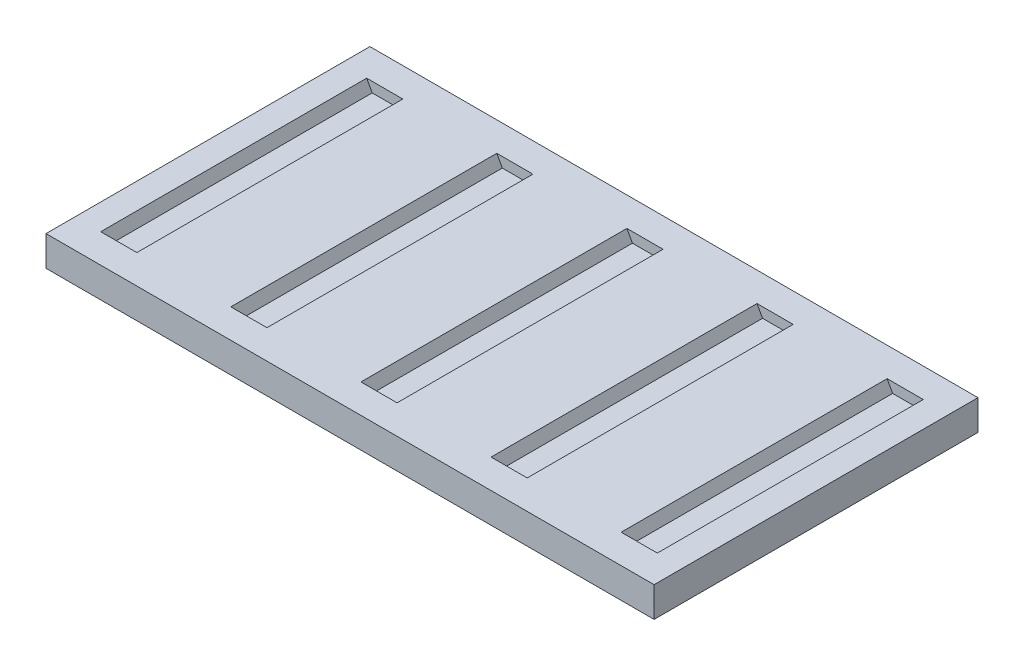
SolidWorks part; units mm, degrees
material "ABS"
ref_plane "Front Plane" through (0, 0, 0) normal (0, 0, 1) x (1, 0, 0)
ref_plane "Top Plane" through (0, 0, 0) normal (0, 1, 0) x (1, 0, 0)
ref_plane "Right Plane" through (0, 0, 0) normal (1, 0, 0) x (0, 0, -1)
sketch "ｽｹｯﾁ1" plane through (0, 0, 0) normal (0, 0, 1) x (1, 0, 0)
  line L0 (0, 0) -> (167.7493, 0) construction
  line B0 (0, 6.1517) -> (0, -7.9464) construction
  line B1 (-3.1032, 0) -> (3.1032, 0)
  line B2 (3.1032, 0) -> (2.3481, -2.0746)
  line B3 (1.0607, -2.976) -> (-1.0607, -2.976)
  line B4 (-2.3481, -2.0746) -> (-3.1032, 0)
  arc B5 (2.3481, -2.0746) -> (1.0607, -2.976) centre (1.0607, -1.606) cw
  arc B6 (-1.0607, -2.976) -> (-2.3481, -2.0746) centre (-1.0607, -1.606) cw
sketch_block_instance "ﾌﾞﾛｯｸ1-1"
sketch_block "ﾌﾞﾛｯｸ1" parameters "D2"=1.37, "D1"=40
sketch "ｽｹｯﾁ3" plane through (0, 0, 0) normal (0, 0, 1) x (1, 0, 0)
  line L0 (0, 6.1517) -> (0, -7.9464) construction
  line L1 (-2.3481, -2.0746) -> (-3.1032, 0) construction
  line L2 (1.0607, -2.976) -> (-1.0607, -2.976) construction
  line L3 (3.1032, 0) -> (2.3481, -2.0746) construction
  line L4 (3.1032, 0) -> (9.5968, 0)
  line L5 (0, 0) -> (167.7493, 0) construction
  line L6 (10.3519, -2.0746) -> (9.5968, 0)
  line L7 (13.7607, -2.976) -> (11.6393, -2.976)
  line L8 (0, 6.1517) -> (0, -7.9464) construction
  line L9 (-2.3481, -2.0746) -> (-3.1032, 0)
  line L10 (1.0607, -2.976) -> (-1.0607, -2.976)
  line L11 (3.1032, 0) -> (2.3481, -2.0746)
  line L12 (15.8032, 0) -> (15.0481, -2.0746)
  line L13 (12.7, 6.1517) -> (12.7, -7.9464) construction
  line L14 (15.8032, 0) -> (22.2968, 0)
  line L15 (23.0519, -2.0746) -> (22.2968, 0)
  line L16 (26.4607, -2.976) -> (24.3393, -2.976)
  line L17 (28.5032, 0) -> (27.7481, -2.0746)
  line L18 (25.4, 6.1517) -> (25.4, -7.9464) construction
  line L19 (28.5032, 0) -> (34.9968, 0)
  line L20 (35.7519, -2.0746) -> (34.9968, 0)
  line L21 (39.1607, -2.976) -> (37.0393, -2.976)
  line L22 (41.2032, 0) -> (40.4481, -2.0746)
  line L23 (38.1, 6.1517) -> (38.1, -7.9464) construction
  line L24 (41.2032, 0) -> (47.6968, 0)
  line L25 (48.4519, -2.0746) -> (47.6968, 0)
  line L26 (51.8607, -2.976) -> (49.7393, -2.976)
  line L27 (53.9032, 0) -> (53.1481, -2.0746)
  line L28 (50.8, 6.1517) -> (50.8, -7.9464) construction
  line L29 (53.9032, 0) -> (60.3968, 0)
  line L30 (61.1519, -2.0746) -> (60.3968, 0)
  line L31 (64.5607, -2.976) -> (62.4393, -2.976)
  line L32 (66.6032, 0) -> (65.8481, -2.0746)
  line L33 (63.5, 6.1517) -> (63.5, -7.9464) construction
  line L34 (66.6032, 0) -> (73.0968, 0)
  line L35 (73.8519, -2.0746) -> (73.0968, 0)
  line L36 (77.2607, -2.976) -> (75.1393, -2.976)
  line L37 (79.3032, 0) -> (78.5481, -2.0746)
  line L38 (76.2, 6.1517) -> (76.2, -7.9464) construction
  line L39 (79.3032, 0) -> (85.7968, 0)
  line L40 (86.5519, -2.0746) -> (85.7968, 0)
  line L41 (89.9607, -2.976) -> (87.8393, -2.976)
  line L42 (92.0032, 0) -> (91.2481, -2.0746)
  line L43 (88.9, 6.1517) -> (88.9, -7.9464) construction
  line L44 (92.0032, 0) -> (98.4968, 0)
  line L45 (99.2519, -2.0746) -> (98.4968, 0)
  line L46 (102.6607, -2.976) -> (100.5393, -2.976)
  line L47 (104.7032, 0) -> (103.9481, -2.0746)
  line L48 (101.6, 6.1517) -> (101.6, -7.9464) construction
  line L49 (104.7032, 0) -> (111.1968, 0)
  line L50 (111.9519, -2.0746) -> (111.1968, 0)
  line L51 (115.3607, -2.976) -> (113.2393, -2.976)
  line L52 (117.4032, 0) -> (116.6481, -2.0746)
  line L53 (114.3, 6.1517) -> (114.3, -7.9464) construction
  line L54 (117.4032, 0) -> (123.8968, 0)
  line L55 (124.6519, -2.0746) -> (123.8968, 0)
  line L56 (128.0607, -2.976) -> (125.9393, -2.976)
  line L57 (130.1032, 0) -> (129.3481, -2.0746)
  line L58 (127, 6.1517) -> (127, -7.9464) construction
  line L59 (130.1032, 0) -> (136.5968, 0)
  line L60 (137.3519, -2.0746) -> (136.5968, 0)
  line L61 (140.7607, -2.976) -> (138.6393, -2.976)
  line L62 (142.8032, 0) -> (142.0481, -2.0746)
  line L63 (139.7, 6.1517) -> (139.7, -7.9464) construction
  line L64 (142.8032, 0) -> (149.2968, 0)
  line L65 (150.0519, -2.0746) -> (149.2968, 0)
  line L66 (153.4607, -2.976) -> (151.3393, -2.976)
  line L67 (155.5032, 0) -> (154.7481, -2.0746)
  line L68 (152.4, 6.1517) -> (152.4, -7.9464) construction
  line L69 (155.5032, 0) -> (161.9968, 0)
  line L70 (162.7519, -2.0746) -> (161.9968, 0)
  line L71 (166.1607, -2.976) -> (164.0393, -2.976)
  line L72 (168.2032, 0) -> (167.4481, -2.0746)
  line L73 (165.1, 6.1517) -> (165.1, -7.9464) construction
  line L74 (168.2032, 0) -> (174.6968, 0)
  line L75 (175.4519, -2.0746) -> (174.6968, 0)
  line L76 (178.8607, -2.976) -> (176.7393, -2.976)
  line L77 (180.9032, 0) -> (180.1481, -2.0746)
  line L78 (177.8, 6.1517) -> (177.8, -7.9464) construction
  line L79 (180.9032, 0) -> (187.3968, 0)
  line L80 (188.1519, -2.0746) -> (187.3968, 0)
  line L81 (191.5607, -2.976) -> (189.4393, -2.976)
  line L82 (193.6032, 0) -> (192.8481, -2.0746)
  line L83 (190.5, 6.1517) -> (190.5, -7.9464) construction
  line L84 (193.6032, 0) -> (200.0968, 0)
  line L85 (200.8519, -2.0746) -> (200.0968, 0)
  line L86 (204.2607, -2.976) -> (202.1393, -2.976)
  line L87 (206.3032, 0) -> (205.5481, -2.0746)
  line L88 (203.2, 6.1517) -> (203.2, -7.9464) construction
  line L89 (206.3032, 0) -> (212.7968, 0)
  line L90 (213.5519, -2.0746) -> (212.7968, 0)
  line L91 (216.9607, -2.976) -> (214.8393, -2.976)
  line L92 (219.0032, 0) -> (218.2481, -2.0746)
  line L93 (215.9, 6.1517) -> (215.9, -7.9464) construction
  line L94 (219.0032, 0) -> (225.4968, 0)
  line L95 (226.2519, -2.0746) -> (225.4968, 0)
  line L96 (229.6607, -2.976) -> (227.5393, -2.976)
  line L97 (231.7032, 0) -> (230.9481, -2.0746)
  line L98 (228.6, 6.1517) -> (228.6, -7.9464) construction
  line L99 (231.7032, 0) -> (238.1968, 0)
  line L100 (238.9519, -2.0746) -> (238.1968, 0)
  line L101 (242.3607, -2.976) -> (240.2393, -2.976)
  line L102 (244.4032, 0) -> (243.6481, -2.0746)
  line L103 (241.3, 6.1517) -> (241.3, -7.9464) construction
  line L104 (244.4032, 0) -> (250.8968, 0)
  arc A0 (-2.3481, -2.0746) -> (-1.0607, -2.976) centre (-1.0607, -1.606) ccw construction
  arc A1 (1.0607, -2.976) -> (2.3481, -2.0746) centre (1.0607, -1.606) ccw construction
  arc A2 (10.3519, -2.0746) -> (11.6393, -2.976) centre (11.6393, -1.606) ccw
  arc A3 (13.7607, -2.976) -> (15.0481, -2.0746) centre (13.7607, -1.606) ccw
  arc A4 (-2.3481, -2.0746) -> (-1.0607, -2.976) centre (-1.0607, -1.606) ccw
  arc A5 (1.0607, -2.976) -> (2.3481, -2.0746) centre (1.0607, -1.606) ccw
  arc A6 (23.0519, -2.0746) -> (24.3393, -2.976) centre (24.3393, -1.606) ccw
  arc A7 (26.4607, -2.976) -> (27.7481, -2.0746) centre (26.4607, -1.606) ccw
  arc A8 (35.7519, -2.0746) -> (37.0393, -2.976) centre (37.0393, -1.606) ccw
  arc A9 (39.1607, -2.976) -> (40.4481, -2.0746) centre (39.1607, -1.606) ccw
  arc A10 (48.4519, -2.0746) -> (49.7393, -2.976) centre (49.7393, -1.606) ccw
  arc A11 (51.8607, -2.976) -> (53.1481, -2.0746) centre (51.8607, -1.606) ccw
  arc A12 (61.1519, -2.0746) -> (62.4393, -2.976) centre (62.4393, -1.606) ccw
  arc A13 (64.5607, -2.976) -> (65.8481, -2.0746) centre (64.5607, -1.606) ccw
  arc A14 (73.8519, -2.0746) -> (75.1393, -2.976) centre (75.1393, -1.606) ccw
  arc A15 (77.2607, -2.976) -> (78.5481, -2.0746) centre (77.2607, -1.606) ccw
  arc A16 (86.5519, -2.0746) -> (87.8393, -2.976) centre (87.8393, -1.606) ccw
  arc A17 (89.9607, -2.976) -> (91.2481, -2.0746) centre (89.9607, -1.606) ccw
  arc A18 (99.2519, -2.0746) -> (100.5393, -2.976) centre (100.5393, -1.606) ccw
  arc A19 (102.6607, -2.976) -> (103.9481, -2.0746) centre (102.6607, -1.606) ccw
  arc A20 (111.9519, -2.0746) -> (113.2393, -2.976) centre (113.2393, -1.606) ccw
  arc A21 (115.3607, -2.976) -> (116.6481, -2.0746) centre (115.3607, -1.606) ccw
  arc A22 (124.6519, -2.0746) -> (125.9393, -2.976) centre (125.9393, -1.606) ccw
  arc A23 (128.0607, -2.976) -> (129.3481, -2.0746) centre (128.0607, -1.606) ccw
  arc A24 (137.3519, -2.0746) -> (138.6393, -2.976) centre (138.6393, -1.606) ccw
  arc A25 (140.7607, -2.976) -> (142.0481, -2.0746) centre (140.7607, -1.606) ccw
  arc A26 (150.0519, -2.0746) -> (151.3393, -2.976) centre (151.3393, -1.606) ccw
  arc A27 (153.4607, -2.976) -> (154.7481, -2.0746) centre (153.4607, -1.606) ccw
  arc A28 (162.7519, -2.0746) -> (164.0393, -2.976) centre (164.0393, -1.606) ccw
  arc A29 (166.1607, -2.976) -> (167.4481, -2.0746) centre (166.1607, -1.606) ccw
  arc A30 (175.4519, -2.0746) -> (176.7393, -2.976) centre (176.7393, -1.606) ccw
  arc A31 (178.8607, -2.976) -> (180.1481, -2.0746) centre (178.8607, -1.606) ccw
  arc A32 (188.1519, -2.0746) -> (189.4393, -2.976) centre (189.4393, -1.606) ccw
  arc A33 (191.5607, -2.976) -> (192.8481, -2.0746) centre (191.5607, -1.606) ccw
  arc A34 (200.8519, -2.0746) -> (202.1393, -2.976) centre (202.1393, -1.606) ccw
  arc A35 (204.2607, -2.976) -> (205.5481, -2.0746) centre (204.2607, -1.606) ccw
  arc A36 (213.5519, -2.0746) -> (214.8393, -2.976) centre (214.8393, -1.606) ccw
  arc A37 (216.9607, -2.976) -> (218.2481, -2.0746) centre (216.9607, -1.606) ccw
  arc A38 (226.2519, -2.0746) -> (227.5393, -2.976) centre (227.5393, -1.606) ccw
  arc A39 (229.6607, -2.976) -> (230.9481, -2.0746) centre (229.6607, -1.606) ccw
  arc A40 (238.9519, -2.0746) -> (240.2393, -2.976) centre (240.2393, -1.606) ccw
  arc A41 (242.3607, -2.976) -> (243.6481, -2.0746) centre (242.3607, -1.606) ccw
  dimension "D1" = 20
  dimension "D2" = 12.7
sketch "ｽｹｯﾁ4" plane through (0, 0, 0) normal (0, 0, 1) x (1, 0, 0)
  line L0 (0, 6.1517) -> (0, -7.9464) construction
  line L1 (1.0607, -2.976) -> (-1.0607, -2.976) construction
  line L2 (3.1032, 0) -> (2.3481, -2.0746) construction
  line L3 (3.1032, 0) -> (9.5968, 0) construction
  line L4 (10.3519, -2.0746) -> (9.5968, 0) construction
  line L5 (13.7607, -2.976) -> (11.6393, -2.976) construction
  line L6 (15.8032, 0) -> (15.0481, -2.0746) construction
  line L7 (15.8032, 0) -> (22.2968, 0) construction
  line L8 (23.0519, -2.0746) -> (22.2968, 0) construction
  line L9 (26.4607, -2.976) -> (24.3393, -2.976) construction
  line L10 (28.5032, 0) -> (27.7481, -2.0746) construction
  line L11 (28.5032, 0) -> (34.9968, 0) construction
  line L12 (35.7519, -2.0746) -> (34.9968, 0) construction
  line L13 (39.1607, -2.976) -> (37.0393, -2.976) construction
  line L14 (41.2032, 0) -> (40.4481, -2.0746) construction
  line L15 (41.2032, 0) -> (47.6968, 0) construction
  line L16 (48.4519, -2.0746) -> (47.6968, 0) construction
  line L17 (51.8607, -2.976) -> (49.7393, -2.976) construction
  line L18 (53.9032, 0) -> (53.1481, -2.0746) construction
  line L19 (53.9032, 0) -> (60.3968, 0) construction
  line L20 (61.1519, -2.0746) -> (60.3968, 0) construction
  line L21 (64.5607, -2.976) -> (62.4393, -2.976) construction
  line L22 (66.6032, 0) -> (65.8481, -2.0746) construction
  line L23 (66.6032, 0) -> (73.0968, 0) construction
  line L24 (73.8519, -2.0746) -> (73.0968, 0) construction
  line L25 (77.2607, -2.976) -> (75.1393, -2.976) construction
  line L26 (79.3032, 0) -> (78.5481, -2.0746) construction
  line L27 (79.3032, 0) -> (85.7968, 0) construction
  line L28 (86.5519, -2.0746) -> (85.7968, 0) construction
  line L29 (89.9607, -2.976) -> (87.8393, -2.976) construction
  line L30 (92.0032, 0) -> (91.2481, -2.0746) construction
  line L31 (92.0032, 0) -> (98.4968, 0) construction
  line L32 (99.2519, -2.0746) -> (98.4968, 0) construction
  line L33 (102.6607, -2.976) -> (100.5393, -2.976) construction
  line L34 (104.7032, 0) -> (103.9481, -2.0746) construction
  line L35 (104.7032, 0) -> (111.1968, 0) construction
  line L36 (111.9519, -2.0746) -> (111.1968, 0) construction
  line L37 (115.3607, -2.976) -> (113.2393, -2.976) construction
  line L38 (117.4032, 0) -> (116.6481, -2.0746) construction
  line L39 (117.4032, 0) -> (123.8968, 0) construction
  line L40 (124.6519, -2.0746) -> (123.8968, 0) construction
  line L41 (128.0607, -2.976) -> (125.9393, -2.976) construction
  line L42 (130.1032, 0) -> (129.3481, -2.0746) construction
  line L43 (130.1032, 0) -> (136.5968, 0) construction
  line L44 (137.3519, -2.0746) -> (136.5968, 0) construction
  line L45 (140.7607, -2.976) -> (138.6393, -2.976) construction
  line L46 (142.8032, 0) -> (142.0481, -2.0746) construction
  line L47 (142.8032, 0) -> (149.2968, 0) construction
  line L48 (150.0519, -2.0746) -> (149.2968, 0) construction
  line L49 (153.4607, -2.976) -> (151.3393, -2.976) construction
  line L50 (155.5032, 0) -> (154.7481, -2.0746) construction
  line L51 (155.5032, 0) -> (161.9968, 0) construction
  line L52 (162.7519, -2.0746) -> (161.9968, 0) construction
  line L53 (166.1607, -2.976) -> (164.0393, -2.976) construction
  line L54 (168.2032, 0) -> (167.4481, -2.0746) construction
  line L55 (168.2032, 0) -> (174.6968, 0) construction
  line L56 (175.4519, -2.0746) -> (174.6968, 0) construction
  line L57 (178.8607, -2.976) -> (176.7393, -2.976) construction
  line L58 (180.9032, 0) -> (180.1481, -2.0746) construction
  line L59 (180.9032, 0) -> (187.3968, 0) construction
  line L60 (188.1519, -2.0746) -> (187.3968, 0) construction
  line L61 (191.5607, -2.976) -> (189.4393, -2.976) construction
  line L62 (193.6032, 0) -> (192.8481, -2.0746) construction
  line L63 (193.6032, 0) -> (200.0968, 0) construction
  line L64 (200.8519, -2.0746) -> (200.0968, 0) construction
  line L65 (204.2607, -2.976) -> (202.1393, -2.976) construction
  line L66 (206.3032, 0) -> (205.5481, -2.0746) construction
  line L67 (206.3032, 0) -> (212.7968, 0) construction
  line L68 (213.5519, -2.0746) -> (212.7968, 0) construction
  line L69 (216.9607, -2.976) -> (214.8393, -2.976) construction
  line L70 (219.0032, 0) -> (218.2481, -2.0746) construction
  line L71 (219.0032, 0) -> (225.4968, 0) construction
  line L72 (226.2519, -2.0746) -> (225.4968, 0) construction
  line L74 (121.1804, 61.4098) -> (121.1804, -57.3786) construction
  line L75 (229.6607, -2.976) -> (227.5393, -2.976) construction
  line L76 (231.7032, 0) -> (230.9481, -2.0746) construction
  line L77 (1.0607, -2.976) -> (0, -2.976)
  line L78 (3.1032, 0) -> (2.3481, -2.0746)
  line L79 (3.1032, 0) -> (9.5968, 0)
  line L80 (10.3519, -2.0746) -> (9.5968, 0)
  line L81 (13.7607, -2.976) -> (11.6393, -2.976)
  line L82 (15.8032, 0) -> (15.0481, -2.0746)
  line L83 (15.8032, 0) -> (22.2968, 0)
  line L84 (23.0519, -2.0746) -> (22.2968, 0)
  line L85 (26.4607, -2.976) -> (24.3393, -2.976)
  line L86 (28.5032, 0) -> (27.7481, -2.0746)
  line L87 (28.5032, 0) -> (34.9968, 0)
  line L88 (35.7519, -2.0746) -> (34.9968, 0)
  line L89 (39.1607, -2.976) -> (37.0393, -2.976)
  line L90 (41.2032, 0) -> (40.4481, -2.0746)
  line L91 (41.2032, 0) -> (47.6968, 0)
  line L92 (48.4519, -2.0746) -> (47.6968, 0)
  line L93 (51.8607, -2.976) -> (49.7393, -2.976)
  line L94 (53.9032, 0) -> (53.1481, -2.0746)
  line L95 (53.9032, 0) -> (60.3968, 0)
  line L96 (61.1519, -2.0746) -> (60.3968, 0)
  line L97 (64.5607, -2.976) -> (62.4393, -2.976)
  line L98 (66.6032, 0) -> (65.8481, -2.0746)
  line L99 (66.6032, 0) -> (73.0968, 0)
  line L100 (73.8519, -2.0746) -> (73.0968, 0)
  line L101 (77.2607, -2.976) -> (75.1393, -2.976)
  line L102 (79.3032, 0) -> (78.5481, -2.0746)
  line L103 (79.3032, 0) -> (85.7968, 0)
  line L104 (86.5519, -2.0746) -> (85.7968, 0)
  line L105 (89.9607, -2.976) -> (87.8393, -2.976)
  line L106 (92.0032, 0) -> (91.2481, -2.0746)
  line L107 (92.0032, 0) -> (98.4968, 0)
  line L108 (99.2519, -2.0746) -> (98.4968, 0)
  line L109 (102.6607, -2.976) -> (100.5393, -2.976)
  line L110 (104.7032, 0) -> (103.9481, -2.0746)
  line L111 (104.7032, 0) -> (111.1968, 0)
  line L112 (111.9519, -2.0746) -> (111.1968, 0)
  line L113 (115.3607, -2.976) -> (113.2393, -2.976)
  line L114 (117.4032, 0) -> (116.6481, -2.0746)
  line L115 (117.4032, 0) -> (123.8968, 0)
  line L116 (124.6519, -2.0746) -> (123.8968, 0)
  line L117 (128.0607, -2.976) -> (125.9393, -2.976)
  line L118 (130.1032, 0) -> (129.3481, -2.0746)
  line L119 (130.1032, 0) -> (136.5968, 0)
  line L120 (137.3519, -2.0746) -> (136.5968, 0)
  line L121 (140.7607, -2.976) -> (138.6393, -2.976)
  line L122 (142.8032, 0) -> (142.0481, -2.0746)
  line L123 (142.8032, 0) -> (149.2968, 0)
  line L124 (150.0519, -2.0746) -> (149.2968, 0)
  line L125 (153.4607, -2.976) -> (151.3393, -2.976)
  line L126 (155.5032, 0) -> (154.7481, -2.0746)
  line L127 (155.5032, 0) -> (161.9968, 0)
  line L128 (162.7519, -2.0746) -> (161.9968, 0)
  line L129 (166.1607, -2.976) -> (164.0393, -2.976)
  line L130 (168.2032, 0) -> (167.4481, -2.0746)
  line L131 (168.2032, 0) -> (174.6968, 0)
  line L132 (175.4519, -2.0746) -> (174.6968, 0)
  line L133 (178.8607, -2.976) -> (176.7393, -2.976)
  line L134 (180.9032, 0) -> (180.1481, -2.0746)
  line L135 (180.9032, 0) -> (187.3968, 0)
  line L136 (188.1519, -2.0746) -> (187.3968, 0)
  line L137 (191.5607, -2.976) -> (189.4393, -2.976)
  line L138 (193.6032, 0) -> (192.8481, -2.0746)
  line L139 (193.6032, 0) -> (200.0968, 0)
  line L140 (200.8519, -2.0746) -> (200.0968, 0)
  line L141 (204.2607, -2.976) -> (202.1393, -2.976)
  line L142 (206.3032, 0) -> (205.5481, -2.0746)
  line L143 (206.3032, 0) -> (212.7968, 0)
  line L144 (213.5519, -2.0746) -> (212.7968, 0)
  line L145 (216.9607, -2.976) -> (214.8393, -2.976)
  line L146 (219.0032, 0) -> (218.2481, -2.0746)
  line L147 (219.0032, 0) -> (225.4968, 0)
  line L148 (226.2519, -2.0746) -> (225.4968, 0)
  line L150 (0, -7) -> (55.8373, -7) construction
  line L151 (242.3607, -2.976) -> (240.2393, -2.976) construction
  line L152 (0, -2.976) -> (0, -15)
  line L153 (0, -15) -> (242.3607, -15)
  line L154 (242.3607, -2.976) -> (242.3607, -15)
  line L155 (238.9519, -2.0746) -> (238.1968, 0) construction
  line L156 (231.7032, 0) -> (238.1968, 0) construction
  line L157 (229.6607, -2.976) -> (227.5393, -2.976)
  line L158 (231.7032, 0) -> (230.9481, -2.0746)
  line L159 (242.3607, -2.976) -> (240.2393, -2.976)
  line L160 (238.9519, -2.0746) -> (238.1968, 0)
  line L161 (231.7032, 0) -> (238.1968, 0)
  arc A0 (229.6607, -2.976) -> (230.9481, -2.0746) centre (229.6607, -1.606) ccw construction
  arc A1 (1.0607, -2.976) -> (2.3481, -2.0746) centre (1.0607, -1.606) ccw construction
  arc A2 (10.3519, -2.0746) -> (11.6393, -2.976) centre (11.6393, -1.606) ccw construction
  arc A3 (13.7607, -2.976) -> (15.0481, -2.0746) centre (13.7607, -1.606) ccw construction
  arc A4 (23.0519, -2.0746) -> (24.3393, -2.976) centre (24.3393, -1.606) ccw construction
  arc A5 (26.4607, -2.976) -> (27.7481, -2.0746) centre (26.4607, -1.606) ccw construction
  arc A6 (35.7519, -2.0746) -> (37.0393, -2.976) centre (37.0393, -1.606) ccw construction
  arc A7 (39.1607, -2.976) -> (40.4481, -2.0746) centre (39.1607, -1.606) ccw construction
  arc A8 (48.4519, -2.0746) -> (49.7393, -2.976) centre (49.7393, -1.606) ccw construction
  arc A9 (51.8607, -2.976) -> (53.1481, -2.0746) centre (51.8607, -1.606) ccw construction
  arc A10 (61.1519, -2.0746) -> (62.4393, -2.976) centre (62.4393, -1.606) ccw construction
  arc A11 (64.5607, -2.976) -> (65.8481, -2.0746) centre (64.5607, -1.606) ccw construction
  arc A12 (73.8519, -2.0746) -> (75.1393, -2.976) centre (75.1393, -1.606) ccw construction
  arc A13 (77.2607, -2.976) -> (78.5481, -2.0746) centre (77.2607, -1.606) ccw construction
  arc A14 (86.5519, -2.0746) -> (87.8393, -2.976) centre (87.8393, -1.606) ccw construction
  arc A15 (89.9607, -2.976) -> (91.2481, -2.0746) centre (89.9607, -1.606) ccw construction
  arc A16 (99.2519, -2.0746) -> (100.5393, -2.976) centre (100.5393, -1.606) ccw construction
  arc A17 (102.6607, -2.976) -> (103.9481, -2.0746) centre (102.6607, -1.606) ccw construction
  arc A18 (111.9519, -2.0746) -> (113.2393, -2.976) centre (113.2393, -1.606) ccw construction
  arc A19 (115.3607, -2.976) -> (116.6481, -2.0746) centre (115.3607, -1.606) ccw construction
  arc A20 (124.6519, -2.0746) -> (125.9393, -2.976) centre (125.9393, -1.606) ccw construction
  arc A21 (128.0607, -2.976) -> (129.3481, -2.0746) centre (128.0607, -1.606) ccw construction
  arc A22 (137.3519, -2.0746) -> (138.6393, -2.976) centre (138.6393, -1.606) ccw construction
  arc A23 (140.7607, -2.976) -> (142.0481, -2.0746) centre (140.7607, -1.606) ccw construction
  arc A24 (150.0519, -2.0746) -> (151.3393, -2.976) centre (151.3393, -1.606) ccw construction
  arc A25 (153.4607, -2.976) -> (154.7481, -2.0746) centre (153.4607, -1.606) ccw construction
  arc A26 (162.7519, -2.0746) -> (164.0393, -2.976) centre (164.0393, -1.606) ccw construction
  arc A27 (166.1607, -2.976) -> (167.4481, -2.0746) centre (166.1607, -1.606) ccw construction
  arc A28 (175.4519, -2.0746) -> (176.7393, -2.976) centre (176.7393, -1.606) ccw construction
  arc A29 (178.8607, -2.976) -> (180.1481, -2.0746) centre (178.8607, -1.606) ccw construction
  arc A30 (188.1519, -2.0746) -> (189.4393, -2.976) centre (189.4393, -1.606) ccw construction
  arc A31 (191.5607, -2.976) -> (192.8481, -2.0746) centre (191.5607, -1.606) ccw construction
  arc A32 (200.8519, -2.0746) -> (202.1393, -2.976) centre (202.1393, -1.606) ccw construction
  arc A33 (204.2607, -2.976) -> (205.5481, -2.0746) centre (204.2607, -1.606) ccw construction
  arc A34 (213.5519, -2.0746) -> (214.8393, -2.976) centre (214.8393, -1.606) ccw construction
  arc A35 (216.9607, -2.976) -> (218.2481, -2.0746) centre (216.9607, -1.606) ccw construction
  arc A36 (226.2519, -2.0746) -> (227.5393, -2.976) centre (227.5393, -1.606) ccw construction
  arc A37 (238.9519, -2.0746) -> (240.2393, -2.976) centre (240.2393, -1.606) ccw construction
  arc A38 (229.6607, -2.976) -> (230.9481, -2.0746) centre (229.6607, -1.606) ccw
  arc A39 (1.0607, -2.976) -> (2.3481, -2.0746) centre (1.0607, -1.606) ccw
  arc A40 (10.3519, -2.0746) -> (11.6393, -2.976) centre (11.6393, -1.606) ccw
  arc A41 (13.7607, -2.976) -> (15.0481, -2.0746) centre (13.7607, -1.606) ccw
  arc A42 (23.0519, -2.0746) -> (24.3393, -2.976) centre (24.3393, -1.606) ccw
  arc A43 (26.4607, -2.976) -> (27.7481, -2.0746) centre (26.4607, -1.606) ccw
  arc A44 (35.7519, -2.0746) -> (37.0393, -2.976) centre (37.0393, -1.606) ccw
  arc A45 (39.1607, -2.976) -> (40.4481, -2.0746) centre (39.1607, -1.606) ccw
  arc A46 (48.4519, -2.0746) -> (49.7393, -2.976) centre (49.7393, -1.606) ccw
  arc A47 (51.8607, -2.976) -> (53.1481, -2.0746) centre (51.8607, -1.606) ccw
  arc A48 (61.1519, -2.0746) -> (62.4393, -2.976) centre (62.4393, -1.606) ccw
  arc A49 (64.5607, -2.976) -> (65.8481, -2.0746) centre (64.5607, -1.606) ccw
  arc A50 (73.8519, -2.0746) -> (75.1393, -2.976) centre (75.1393, -1.606) ccw
  arc A51 (77.2607, -2.976) -> (78.5481, -2.0746) centre (77.2607, -1.606) ccw
  arc A52 (86.5519, -2.0746) -> (87.8393, -2.976) centre (87.8393, -1.606) ccw
  arc A53 (89.9607, -2.976) -> (91.2481, -2.0746) centre (89.9607, -1.606) ccw
  arc A54 (99.2519, -2.0746) -> (100.5393, -2.976) centre (100.5393, -1.606) ccw
  arc A55 (102.6607, -2.976) -> (103.9481, -2.0746) centre (102.6607, -1.606) ccw
  arc A56 (111.9519, -2.0746) -> (113.2393, -2.976) centre (113.2393, -1.606) ccw
  arc A57 (115.3607, -2.976) -> (116.6481, -2.0746) centre (115.3607, -1.606) ccw
  arc A58 (124.6519, -2.0746) -> (125.9393, -2.976) centre (125.9393, -1.606) ccw
  arc A59 (128.0607, -2.976) -> (129.3481, -2.0746) centre (128.0607, -1.606) ccw
  arc A60 (137.3519, -2.0746) -> (138.6393, -2.976) centre (138.6393, -1.606) ccw
  arc A61 (140.7607, -2.976) -> (142.0481, -2.0746) centre (140.7607, -1.606) ccw
  arc A62 (150.0519, -2.0746) -> (151.3393, -2.976) centre (151.3393, -1.606) ccw
  arc A63 (153.4607, -2.976) -> (154.7481, -2.0746) centre (153.4607, -1.606) ccw
  arc A64 (162.7519, -2.0746) -> (164.0393, -2.976) centre (164.0393, -1.606) ccw
  arc A65 (166.1607, -2.976) -> (167.4481, -2.0746) centre (166.1607, -1.606) ccw
  arc A66 (175.4519, -2.0746) -> (176.7393, -2.976) centre (176.7393, -1.606) ccw
  arc A67 (178.8607, -2.976) -> (180.1481, -2.0746) centre (178.8607, -1.606) ccw
  arc A68 (188.1519, -2.0746) -> (189.4393, -2.976) centre (189.4393, -1.606) ccw
  arc A69 (191.5607, -2.976) -> (192.8481, -2.0746) centre (191.5607, -1.606) ccw
  arc A70 (200.8519, -2.0746) -> (202.1393, -2.976) centre (202.1393, -1.606) ccw
  arc A71 (204.2607, -2.976) -> (205.5481, -2.0746) centre (204.2607, -1.606) ccw
  arc A72 (213.5519, -2.0746) -> (214.8393, -2.976) centre (214.8393, -1.606) ccw
  arc A73 (216.9607, -2.976) -> (218.2481, -2.0746) centre (216.9607, -1.606) ccw
  arc A74 (226.2519, -2.0746) -> (227.5393, -2.976) centre (227.5393, -1.606) ccw
  arc A75 (238.9519, -2.0746) -> (240.2393, -2.976) centre (240.2393, -1.606) ccw
  point P11 (25, -7)
  point P17 (85, -7)
  point P29 (157.3607, -7)
  point P31 (217.3607, -7)
  dimension "D1" = 15
  dimension "D2" = 7
  dimension "D3" = 25
  dimension "D4" = 85
ref_plane "平面1" through (0, 0, -1.55) normal (0, 0, 1) x (1, 0, 0)
sketch "ｽｹｯﾁ5" plane through (0, 0, -1.55) normal (0, 0, 1) x (1, 0, 0)
  line L76 (229.6607, -2.976) -> (227.5393, -2.976)
  line L77 (242.3607, -15) -> (242.3607, -2.976)
  line L78 (0, -15) -> (242.3607, -15)
  line L79 (0, -2.976) -> (0, -15)
  line L80 (1.0607, -2.976) -> (0, -2.976)
  line L81 (3.1032, 0) -> (2.3481, -2.0746)
  line L82 (9.5968, 0) -> (3.1032, 0)
  line L83 (10.3519, -2.0746) -> (9.5968, 0)
  line L84 (13.7607, -2.976) -> (11.6393, -2.976)
  line L85 (15.8032, 0) -> (15.0481, -2.0746)
  line L86 (22.2968, 0) -> (15.8032, 0)
  line L87 (23.0519, -2.0746) -> (22.2968, 0)
  line L88 (26.4607, -2.976) -> (24.3393, -2.976)
  line L89 (28.5032, 0) -> (27.7481, -2.0746)
  line L90 (34.9968, 0) -> (28.5032, 0)
  line L91 (35.7519, -2.0746) -> (34.9968, 0)
  line L92 (39.1607, -2.976) -> (37.0393, -2.976)
  line L93 (41.2032, 0) -> (40.4481, -2.0746)
  line L94 (47.6968, 0) -> (41.2032, 0)
  line L95 (48.4519, -2.0746) -> (47.6968, 0)
  line L96 (51.8607, -2.976) -> (49.7393, -2.976)
  line L97 (53.9032, 0) -> (53.1481, -2.0746)
  line L98 (60.3968, 0) -> (53.9032, 0)
  line L99 (61.1519, -2.0746) -> (60.3968, 0)
  line L100 (64.5607, -2.976) -> (62.4393, -2.976)
  line L101 (66.6032, 0) -> (65.8481, -2.0746)
  line L102 (73.0968, 0) -> (66.6032, 0)
  line L103 (73.8519, -2.0746) -> (73.0968, 0)
  line L104 (77.2607, -2.976) -> (75.1393, -2.976)
  line L105 (79.3032, 0) -> (78.5481, -2.0746)
  line L106 (85.7968, 0) -> (79.3032, 0)
  line L107 (86.5519, -2.0746) -> (85.7968, 0)
  line L108 (89.9607, -2.976) -> (87.8393, -2.976)
  line L109 (92.0032, 0) -> (91.2481, -2.0746)
  line L110 (98.4968, 0) -> (92.0032, 0)
  line L111 (99.2519, -2.0746) -> (98.4968, 0)
  line L112 (102.6607, -2.976) -> (100.5393, -2.976)
  line L113 (104.7032, 0) -> (103.9481, -2.0746)
  line L114 (111.1968, 0) -> (104.7032, 0)
  line L115 (111.9519, -2.0746) -> (111.1968, 0)
  line L116 (115.3607, -2.976) -> (113.2393, -2.976)
  line L117 (117.4032, 0) -> (116.6481, -2.0746)
  line L118 (123.8968, 0) -> (117.4032, 0)
  line L119 (124.6519, -2.0746) -> (123.8968, 0)
  line L120 (128.0607, -2.976) -> (125.9393, -2.976)
  line L121 (130.1032, 0) -> (129.3481, -2.0746)
  line L122 (136.5968, 0) -> (130.1032, 0)
  line L123 (137.3519, -2.0746) -> (136.5968, 0)
  line L124 (140.7607, -2.976) -> (138.6393, -2.976)
  line L125 (142.8032, 0) -> (142.0481, -2.0746)
  line L126 (149.2968, 0) -> (142.8032, 0)
  line L127 (150.0519, -2.0746) -> (149.2968, 0)
  line L128 (153.4607, -2.976) -> (151.3393, -2.976)
  line L129 (155.5032, 0) -> (154.7481, -2.0746)
  line L130 (161.9968, 0) -> (155.5032, 0)
  line L131 (162.7519, -2.0746) -> (161.9968, 0)
  line L132 (166.1607, -2.976) -> (164.0393, -2.976)
  line L133 (168.2032, 0) -> (167.4481, -2.0746)
  line L134 (174.6968, 0) -> (168.2032, 0)
  line L135 (175.4519, -2.0746) -> (174.6968, 0)
  line L136 (178.8607, -2.976) -> (176.7393, -2.976)
  line L137 (180.9032, 0) -> (180.1481, -2.0746)
  line L138 (187.3968, 0) -> (180.9032, 0)
  line L139 (188.1519, -2.0746) -> (187.3968, 0)
  line L140 (191.5607, -2.976) -> (189.4393, -2.976)
  line L141 (193.6032, 0) -> (192.8481, -2.0746)
  line L142 (200.0968, 0) -> (193.6032, 0)
  line L143 (200.8519, -2.0746) -> (200.0968, 0)
  line L144 (204.2607, -2.976) -> (202.1393, -2.976)
  line L145 (206.3032, 0) -> (205.5481, -2.0746)
  line L146 (212.7968, 0) -> (206.3032, 0)
  line L147 (213.5519, -2.0746) -> (212.7968, 0)
  line L148 (216.9607, -2.976) -> (214.8393, -2.976)
  line L149 (219.0032, 0) -> (218.2481, -2.0746)
  line L150 (225.4968, 0) -> (219.0032, 0)
  line L151 (226.2519, -2.0746) -> (225.4968, 0)
  line L153 (242.3607, -15) -> (242.3607, -2.976)
  line L154 (0, -15) -> (242.3607, -15)
  line L155 (0, -2.976) -> (0, -15)
  line L156 (1.0607, -2.976) -> (0, -2.976)
  line L157 (3.1032, 0) -> (2.3481, -2.0746)
  line L158 (9.5968, 0) -> (3.1032, 0)
  line L159 (10.3519, -2.0746) -> (9.5968, 0)
  line L160 (13.7607, -2.976) -> (11.6393, -2.976)
  line L161 (15.8032, 0) -> (15.0481, -2.0746)
  line L162 (22.2968, 0) -> (15.8032, 0)
  line L163 (23.0519, -2.0746) -> (22.2968, 0)
  line L164 (26.4607, -2.976) -> (24.3393, -2.976)
  line L165 (28.5032, 0) -> (27.7481, -2.0746)
  line L166 (34.9968, 0) -> (28.5032, 0)
  line L167 (35.7519, -2.0746) -> (34.9968, 0)
  line L168 (39.1607, -2.976) -> (37.0393, -2.976)
  line L169 (41.2032, 0) -> (40.4481, -2.0746)
  line L170 (47.6968, 0) -> (41.2032, 0)
  line L171 (48.4519, -2.0746) -> (47.6968, 0)
  line L172 (51.8607, -2.976) -> (49.7393, -2.976)
  line L173 (53.9032, 0) -> (53.1481, -2.0746)
  line L174 (60.3968, 0) -> (53.9032, 0)
  line L175 (61.1519, -2.0746) -> (60.3968, 0)
  line L176 (64.5607, -2.976) -> (62.4393, -2.976)
  line L177 (66.6032, 0) -> (65.8481, -2.0746)
  line L178 (73.0968, 0) -> (66.6032, 0)
  line L179 (73.8519, -2.0746) -> (73.0968, 0)
  line L180 (77.2607, -2.976) -> (75.1393, -2.976)
  line L181 (79.3032, 0) -> (78.5481, -2.0746)
  line L182 (85.7968, 0) -> (79.3032, 0)
  line L183 (86.5519, -2.0746) -> (85.7968, 0)
  line L184 (89.9607, -2.976) -> (87.8393, -2.976)
  line L185 (92.0032, 0) -> (91.2481, -2.0746)
  line L186 (98.4968, 0) -> (92.0032, 0)
  line L187 (99.2519, -2.0746) -> (98.4968, 0)
  line L188 (102.6607, -2.976) -> (100.5393, -2.976)
  line L189 (104.7032, 0) -> (103.9481, -2.0746)
  line L190 (111.1968, 0) -> (104.7032, 0)
  line L191 (111.9519, -2.0746) -> (111.1968, 0)
  line L192 (115.3607, -2.976) -> (113.2393, -2.976)
  line L193 (117.4032, 0) -> (116.6481, -2.0746)
  line L194 (123.8968, 0) -> (117.4032, 0)
  line L195 (124.6519, -2.0746) -> (123.8968, 0)
  line L196 (128.0607, -2.976) -> (125.9393, -2.976)
  line L197 (130.1032, 0) -> (129.3481, -2.0746)
  line L198 (136.5968, 0) -> (130.1032, 0)
  line L199 (137.3519, -2.0746) -> (136.5968, 0)
  line L200 (140.7607, -2.976) -> (138.6393, -2.976)
  line L201 (142.8032, 0) -> (142.0481, -2.0746)
  line L202 (149.2968, 0) -> (142.8032, 0)
  line L203 (150.0519, -2.0746) -> (149.2968, 0)
  line L204 (153.4607, -2.976) -> (151.3393, -2.976)
  line L205 (155.5032, 0) -> (154.7481, -2.0746)
  line L206 (161.9968, 0) -> (155.5032, 0)
  line L207 (162.7519, -2.0746) -> (161.9968, 0)
  line L208 (166.1607, -2.976) -> (164.0393, -2.976)
  line L209 (168.2032, 0) -> (167.4481, -2.0746)
  line L210 (174.6968, 0) -> (168.2032, 0)
  line L211 (175.4519, -2.0746) -> (174.6968, 0)
  line L212 (178.8607, -2.976) -> (176.7393, -2.976)
  line L213 (180.9032, 0) -> (180.1481, -2.0746)
  line L214 (187.3968, 0) -> (180.9032, 0)
  line L215 (188.1519, -2.0746) -> (187.3968, 0)
  line L216 (191.5607, -2.976) -> (189.4393, -2.976)
  line L217 (193.6032, 0) -> (192.8481, -2.0746)
  line L218 (200.0968, 0) -> (193.6032, 0)
  line L219 (200.8519, -2.0746) -> (200.0968, 0)
  line L220 (204.2607, -2.976) -> (202.1393, -2.976)
  line L221 (206.3032, 0) -> (205.5481, -2.0746)
  line L222 (212.7968, 0) -> (206.3032, 0)
  line L223 (213.5519, -2.0746) -> (212.7968, 0)
  line L224 (216.9607, -2.976) -> (214.8393, -2.976)
  line L225 (219.0032, 0) -> (218.2481, -2.0746)
  line L226 (225.4968, 0) -> (219.0032, 0)
  line L227 (226.2519, -2.0746) -> (225.4968, 0)
  line L232 (229.6607, -2.976) -> (227.5393, -2.976)
  line L233 (231.7032, 0) -> (230.9481, -2.0746)
  line L234 (231.7032, 0) -> (230.9481, -2.0746)
  line L235 (238.1968, 0) -> (231.7032, 0)
  line L236 (238.1968, 0) -> (231.7032, 0)
  line L237 (238.9519, -2.0746) -> (238.1968, 0)
  line L238 (238.9519, -2.0746) -> (238.1968, 0)
  line L239 (242.3607, -2.976) -> (240.2393, -2.976)
  line L240 (242.3607, -2.976) -> (240.2393, -2.976)
  arc A36 (1.0607, -2.976) -> (2.3481, -2.0746) centre (1.0607, -1.606) ccw
  arc A37 (10.3519, -2.0746) -> (11.6393, -2.976) centre (11.6393, -1.606) ccw
  arc A38 (13.7607, -2.976) -> (15.0481, -2.0746) centre (13.7607, -1.606) ccw
  arc A39 (23.0519, -2.0746) -> (24.3393, -2.976) centre (24.3393, -1.606) ccw
  arc A40 (26.4607, -2.976) -> (27.7481, -2.0746) centre (26.4607, -1.606) ccw
  arc A41 (35.7519, -2.0746) -> (37.0393, -2.976) centre (37.0393, -1.606) ccw
  arc A42 (39.1607, -2.976) -> (40.4481, -2.0746) centre (39.1607, -1.606) ccw
  arc A43 (48.4519, -2.0746) -> (49.7393, -2.976) centre (49.7393, -1.606) ccw
  arc A44 (51.8607, -2.976) -> (53.1481, -2.0746) centre (51.8607, -1.606) ccw
  arc A45 (61.1519, -2.0746) -> (62.4393, -2.976) centre (62.4393, -1.606) ccw
  arc A46 (64.5607, -2.976) -> (65.8481, -2.0746) centre (64.5607, -1.606) ccw
  arc A47 (73.8519, -2.0746) -> (75.1393, -2.976) centre (75.1393, -1.606) ccw
  arc A48 (77.2607, -2.976) -> (78.5481, -2.0746) centre (77.2607, -1.606) ccw
  arc A49 (86.5519, -2.0746) -> (87.8393, -2.976) centre (87.8393, -1.606) ccw
  arc A50 (89.9607, -2.976) -> (91.2481, -2.0746) centre (89.9607, -1.606) ccw
  arc A51 (99.2519, -2.0746) -> (100.5393, -2.976) centre (100.5393, -1.606) ccw
  arc A52 (102.6607, -2.976) -> (103.9481, -2.0746) centre (102.6607, -1.606) ccw
  arc A53 (111.9519, -2.0746) -> (113.2393, -2.976) centre (113.2393, -1.606) ccw
  arc A54 (115.3607, -2.976) -> (116.6481, -2.0746) centre (115.3607, -1.606) ccw
  arc A55 (124.6519, -2.0746) -> (125.9393, -2.976) centre (125.9393, -1.606) ccw
  arc A56 (128.0607, -2.976) -> (129.3481, -2.0746) centre (128.0607, -1.606) ccw
  arc A57 (137.3519, -2.0746) -> (138.6393, -2.976) centre (138.6393, -1.606) ccw
  arc A58 (140.7607, -2.976) -> (142.0481, -2.0746) centre (140.7607, -1.606) ccw
  arc A59 (150.0519, -2.0746) -> (151.3393, -2.976) centre (151.3393, -1.606) ccw
  arc A60 (153.4607, -2.976) -> (154.7481, -2.0746) centre (153.4607, -1.606) ccw
  arc A61 (162.7519, -2.0746) -> (164.0393, -2.976) centre (164.0393, -1.606) ccw
  arc A62 (166.1607, -2.976) -> (167.4481, -2.0746) centre (166.1607, -1.606) ccw
  arc A63 (175.4519, -2.0746) -> (176.7393, -2.976) centre (176.7393, -1.606) ccw
  arc A64 (178.8607, -2.976) -> (180.1481, -2.0746) centre (178.8607, -1.606) ccw
  arc A65 (188.1519, -2.0746) -> (189.4393, -2.976) centre (189.4393, -1.606) ccw
  arc A66 (191.5607, -2.976) -> (192.8481, -2.0746) centre (191.5607, -1.606) ccw
  arc A67 (200.8519, -2.0746) -> (202.1393, -2.976) centre (202.1393, -1.606) ccw
  arc A68 (204.2607, -2.976) -> (205.5481, -2.0746) centre (204.2607, -1.606) ccw
  arc A69 (213.5519, -2.0746) -> (214.8393, -2.976) centre (214.8393, -1.606) ccw
  arc A70 (216.9607, -2.976) -> (218.2481, -2.0746) centre (216.9607, -1.606) ccw
  arc A71 (226.2519, -2.0746) -> (227.5393, -2.976) centre (227.5393, -1.606) ccw
  arc A72 (1.0607, -2.976) -> (2.3481, -2.0746) centre (1.0607, -1.606) ccw
  arc A73 (10.3519, -2.0746) -> (11.6393, -2.976) centre (11.6393, -1.606) ccw
  arc A74 (13.7607, -2.976) -> (15.0481, -2.0746) centre (13.7607, -1.606) ccw
  arc A75 (23.0519, -2.0746) -> (24.3393, -2.976) centre (24.3393, -1.606) ccw
  arc A76 (26.4607, -2.976) -> (27.7481, -2.0746) centre (26.4607, -1.606) ccw
  arc A77 (35.7519, -2.0746) -> (37.0393, -2.976) centre (37.0393, -1.606) ccw
  arc A78 (39.1607, -2.976) -> (40.4481, -2.0746) centre (39.1607, -1.606) ccw
  arc A79 (48.4519, -2.0746) -> (49.7393, -2.976) centre (49.7393, -1.606) ccw
  arc A80 (51.8607, -2.976) -> (53.1481, -2.0746) centre (51.8607, -1.606) ccw
  arc A81 (61.1519, -2.0746) -> (62.4393, -2.976) centre (62.4393, -1.606) ccw
  arc A82 (64.5607, -2.976) -> (65.8481, -2.0746) centre (64.5607, -1.606) ccw
  arc A83 (73.8519, -2.0746) -> (75.1393, -2.976) centre (75.1393, -1.606) ccw
  arc A84 (77.2607, -2.976) -> (78.5481, -2.0746) centre (77.2607, -1.606) ccw
  arc A85 (86.5519, -2.0746) -> (87.8393, -2.976) centre (87.8393, -1.606) ccw
  arc A86 (89.9607, -2.976) -> (91.2481, -2.0746) centre (89.9607, -1.606) ccw
  arc A87 (99.2519, -2.0746) -> (100.5393, -2.976) centre (100.5393, -1.606) ccw
  arc A88 (102.6607, -2.976) -> (103.9481, -2.0746) centre (102.6607, -1.606) ccw
  arc A89 (111.9519, -2.0746) -> (113.2393, -2.976) centre (113.2393, -1.606) ccw
  arc A90 (115.3607, -2.976) -> (116.6481, -2.0746) centre (115.3607, -1.606) ccw
  arc A91 (124.6519, -2.0746) -> (125.9393, -2.976) centre (125.9393, -1.606) ccw
  arc A92 (128.0607, -2.976) -> (129.3481, -2.0746) centre (128.0607, -1.606) ccw
  arc A93 (137.3519, -2.0746) -> (138.6393, -2.976) centre (138.6393, -1.606) ccw
  arc A94 (140.7607, -2.976) -> (142.0481, -2.0746) centre (140.7607, -1.606) ccw
  arc A95 (150.0519, -2.0746) -> (151.3393, -2.976) centre (151.3393, -1.606) ccw
  arc A96 (153.4607, -2.976) -> (154.7481, -2.0746) centre (153.4607, -1.606) ccw
  arc A97 (162.7519, -2.0746) -> (164.0393, -2.976) centre (164.0393, -1.606) ccw
  arc A98 (166.1607, -2.976) -> (167.4481, -2.0746) centre (166.1607, -1.606) ccw
  arc A99 (175.4519, -2.0746) -> (176.7393, -2.976) centre (176.7393, -1.606) ccw
  arc A100 (178.8607, -2.976) -> (180.1481, -2.0746) centre (178.8607, -1.606) ccw
  arc A101 (188.1519, -2.0746) -> (189.4393, -2.976) centre (189.4393, -1.606) ccw
  arc A102 (191.5607, -2.976) -> (192.8481, -2.0746) centre (191.5607, -1.606) ccw
  arc A103 (200.8519, -2.0746) -> (202.1393, -2.976) centre (202.1393, -1.606) ccw
  arc A104 (204.2607, -2.976) -> (205.5481, -2.0746) centre (204.2607, -1.606) ccw
  arc A105 (213.5519, -2.0746) -> (214.8393, -2.976) centre (214.8393, -1.606) ccw
  arc A106 (216.9607, -2.976) -> (218.2481, -2.0746) centre (216.9607, -1.606) ccw
  arc A107 (226.2519, -2.0746) -> (227.5393, -2.976) centre (227.5393, -1.606) ccw
  arc A110 (229.6607, -2.976) -> (230.9481, -2.0746) centre (229.6607, -1.606) ccw
  arc A111 (229.6607, -2.976) -> (230.9481, -2.0746) centre (229.6607, -1.606) ccw
  arc A112 (238.9519, -2.0746) -> (240.2393, -2.976) centre (240.2393, -1.606) ccw
  arc A113 (238.9519, -2.0746) -> (240.2393, -2.976) centre (240.2393, -1.606) ccw
  dimension "D1" = 0
extrude "ﾎﾞｽ - 押し出し1" add sketch "ｽｹｯﾁ5" against normal blind 60
hole_wizard "M4x0.7 ねじ穴1" [suppressed] positions "ｽｹｯﾁ6" profile "ｽｹｯﾁ8" tap size "M4x0.7" standard "JIS"
sketch "ｽｹｯﾁ6" plane through (0, 0, -1.55) normal (0, 0, 1) x (1, 0, 0)
  point P0 (85, -7)
  point P3 (25, -7)
  point P6 (145, -7)
  point P9 (205, -7)
sketch "ｽｹｯﾁ8" plane through (85, -7, -1.55) normal (1, 0, 0) x (0, -1, 0)
  line L0 (0, 0) -> (0, 19.2)
  line L1 (0, 19.2) -> (1.65, 19.2)
  line L2 (1.65, 19.2) -> (1.65, 0)
  line L5 (1.65, 0) -> (0, 0)
  line L11 (0, -6.35) -> (0, 107.95) construction
  dimension "ねじ山の主要直径" = 3.3
  dimension "次ｻｰﾌｪｽまでのねじ下穴ﾄﾞﾘﾙの深さ" = 19.2
sketch "ｽｹｯﾁ9" plane through (0, 0, -61.55) normal (0, 0, -1) x (-1, 0, 0)
  line L0 (-242.3607, -15) -> (-242.3607, -2.976) construction
  line L1 (0, -15) -> (-242.3607, -15)
  line L2 (0, -15) -> (0, 2.5)
  line L3 (0, 2.5) -> (-242.3607, 2.5)
  line L4 (-242.3607, -15) -> (-242.3607, 2.5)
  line L5 (0, -15) -> (-242.3607, 2.5) construction
  line L6 (0, 2.5) -> (-242.3607, -15) construction
  line L7 (-121.1804, 40.7463) -> (-121.1804, -32.6873) construction
  line L8 (-121.1804, 61.4098) -> (-121.1804, -57.3786) construction
  circle A0 centre (-25, -7) radius 2.1
  circle A1 centre (-85, -7) radius 2.1
  circle A2 centre (-157.3607, -7) radius 2.1
  circle A3 centre (-217.3607, -7) radius 2.1
  point P10 (-121.1804, -6.25)
  dimension "D1" = 4.2
  dimension "D2" = 17.5
extrude "ﾎﾞｽ - 押し出し2" add sketch "ｽｹｯﾁ9" along normal blind 3 separate body
sketch "ｽｹｯﾁ10" plane through (0, -15, 0) normal (0, -1, 0) x (1, 0, 0)
  line L0 (0, -31.55) -> (242.3607, -31.55) construction
  line L1 (0, -61.55) -> (0, -1.55) construction
  line L2 (242.3607, -61.55) -> (242.3607, -1.55) construction
  line L3 (121.1804, -31.55) -> (121.1804, 46.2748) construction
  circle A0 centre (7, -31.55) radius 2.1
  circle A1 centre (235.3607, -31.55) radius 2.1
  circle A2 centre (121.5, -31.55) radius 2.1
  dimension "D1" = 4.2
  dimension "D2" = 7
  dimension "D3" = 4.2
  dimension "D4" = 121.5
hole_wizard "M4x0.7 ねじ穴2" [suppressed] positions "ｽｹｯﾁ11" profile "ｽｹｯﾁ12" tap size "M4x0.7" standard "JIS"
sketch "ｽｹｯﾁ11" plane through (0, -15, 0) normal (0, -1, 0) x (-1, 0, 0)
  point P0 (-7, 11.15)
  point P3 (-121.5, 11.15)
  point P6 (-223, 11.15)
sketch "ｽｹｯﾁ12" plane through (7, -15, -11.15) normal (1, 0, 0) x (0, 0, -1)
  line L0 (0, 0) -> (0, 12.4914)
  line L1 (0, 12.4914) -> (1.65, 11.5)
  line L2 (1.65, 11.5) -> (1.65, 0)
  line L5 (1.65, 0) -> (0, 0)
  line L10 (0, 12.4914) -> (-1.65, 11.5) construction
  line L11 (0, -6.35) -> (0, 107.95) construction
  dimension "ねじ下穴ﾄﾞﾘﾙ直径" = 3.3
  dimension "ねじ下穴ﾄﾞﾘﾙの深さ" = 11.5
  dimension "ﾄﾞﾘﾙ角度" = 118
sketch "ｽｹｯﾁ13" plane through (0, 0, 0) normal (0, 0, 1) x (1, 0, 0)
  line L0 (0, 1) -> (242.3607, 1)
  line L1 (219.0032, 0) -> (225.4968, 0) construction
  line L4 (0, -15) -> (242.3607, -15)
  line L5 (242.3607, -15) -> (242.3607, 2.5)
  line L6 (242.3607, 2.5) -> (0, 2.5)
  line L7 (0, 2.5) -> (0, -15)
  line L8 (0, -15) -> (242.3607, -15)
  line L9 (242.3607, -15) -> (242.3607, 1)
  line L11 (0, 1) -> (0, -15)
  circle A1 centre (85, -7) radius 2.1
  circle A2 centre (85, -7) radius 2.1
  circle A3 centre (25, -7) radius 2.1
  circle A4 centre (25, -7) radius 2.1
  circle A5 centre (217.3607, -7) radius 2.1
  circle A6 centre (217.3607, -7) radius 2.1
  circle A7 centre (157.3607, -7) radius 2.1
  circle A8 centre (157.3607, -7) radius 2.1
  dimension "D6" = 1
  dimension "D1" = 0
  dimension "D2" = 0
  dimension "D3" = 0
  dimension "D4" = 0
  dimension "D5" = 0
extrude "ﾎﾞｽ - 押し出し3" add sketch "ｽｹｯﾁ13" along normal mid plane 3.1 separate body
mirror "ﾐﾗｰ1" about plane through (0, 0, 0) normal (0, 0, 1) of bodies 101 103 104
sketch "ｽｹｯﾁ14" plane through (0, -15, 0) normal (0, -1, 0) x (1, 0, 0)
  line L0 (0, 0) -> (-12.3693, 0) construction
  line L1 (242.3607, -64.55) -> (0, -64.55)
  line L2 (242.3607, -64.55) -> (242.3607, 64.55)
  line L3 (242.3607, 64.55) -> (0, 64.55)
  line L4 (0, -64.55) -> (0, 64.55)
  line L5 (242.3607, -64.55) -> (0, 64.55) construction
  line L6 (242.3607, 64.55) -> (0, -64.55) construction
  circle A0 centre (7, 31.55) radius 2.1
  circle A1 centre (121.5, -31.55) radius 2.1
  circle A2 centre (121.5, -31.55) radius 2.1
  circle A3 centre (235.3607, -31.55) radius 2.1
  circle A4 centre (235.3607, -31.55) radius 2.1
  circle A5 centre (7, -31.55) radius 2.1
  circle A6 centre (7, -31.55) radius 2.1
  circle A7 centre (235.3607, 31.55) radius 2.1
  circle A8 centre (121.5, 31.55) radius 2.1
  point P13 (121.1804, 0)
  dimension "D1" = 0
  dimension "D2" = 0
  dimension "D3" = 0
extrude "ﾎﾞｽ - 押し出し4" add sketch "ｽｹｯﾁ14" along normal blind 3 separate body
combine bodies "組み合わせ2" operation type add bodies to combine 106 101 107 108 105 103
sketch "ｽｹｯﾁ15" plane through (0, 0, -64.55) normal (0, 0, -1) x (-1, 0, 0)
  line L0 (-216.9607, -2.976) -> (-214.8393, -2.976) construction
  line L1 (-228.5688, -2.976) -> (-5.9277, -2.976)
  line L2 (-228.5688, -2.976) -> (-228.5688, -12.2757)
  line L3 (-228.5688, -12.2757) -> (-5.9277, -12.2757)
  line L4 (-5.9277, -2.976) -> (-5.9277, -12.2757)
  line L5 (-228.5688, -2.976) -> (-5.9277, -12.2757) construction
  line L6 (-228.5688, -12.2757) -> (-5.9277, -2.976) construction
  point P4 (-117.2482, -7.6259)
extrude "ﾎﾞｽ - 押し出し5" add sketch "ｽｹｯﾁ15" against normal up to surface (129.1 mm away) up to face at (159.4607, -7, 64.55)
sketch "ｽｹｯﾁ16" plane through (0, -18, 0) normal (0, -1, 0) x (1, 0, 0)
  line L0 (0, 64.55) -> (0, -64.55) construction
  line L1 (0, 17.8023) -> (242.3607, 17.8023)
  line L2 (0, 17.8023) -> (0, -15.4109)
  line L3 (0, -15.4109) -> (242.3607, -15.4109)
  line L4 (242.3607, 17.8023) -> (242.3607, -15.4109)
  line L5 (0, 17.8023) -> (242.3607, -15.4109) construction
  line L6 (0, -15.4109) -> (242.3607, 17.8023) construction
  line L7 (242.3607, -64.55) -> (242.3607, 64.55) construction
  point P4 (121.1804, 1.1957)
extrude "ﾎﾞｽ - 押し出し6" add sketch "ｽｹｯﾁ16" against normal blind 3
sketch "ｽｹｯﾁ17" plane through (0, 0, 0) normal (0, 0, 1) x (1, 0, 0)
  line L0 (0, 0) -> (242.3607, 0) construction
  line L1 (6.9604, 0) -> (27.9604, 0)
  line L2 (27.9604, 0) -> (22.4604, -10)
  line L3 (22.4604, -10) -> (12.4604, -10)
  line L4 (12.4604, -10) -> (6.9604, 0)
  line L5 (17.4604, -10) -> (17.4604, 0) construction
  line L6 (58.8204, 0) -> (79.8204, 0)
  line L7 (69.3204, -10) -> (69.3204, 0) construction
  line L8 (64.3204, -10) -> (58.8204, 0)
  line L9 (79.8204, 0) -> (74.3204, -10)
  line L10 (74.3204, -10) -> (64.3204, -10)
  line L11 (110.6804, 0) -> (131.6804, 0)
  line L12 (121.1804, -10) -> (121.1804, 0) construction
  line L13 (116.1804, -10) -> (110.6804, 0)
  line L14 (131.6804, 0) -> (126.1804, -10)
  line L15 (126.1804, -10) -> (116.1804, -10)
  line L16 (162.5404, 0) -> (183.5404, 0)
  line L17 (173.0404, -10) -> (173.0404, 0) construction
  line L18 (168.0404, -10) -> (162.5404, 0)
  line L19 (183.5404, 0) -> (178.0404, -10)
  line L20 (178.0404, -10) -> (168.0404, -10)
  line L21 (214.4004, 0) -> (235.4004, 0)
  line L22 (224.9004, -10) -> (224.9004, 0) construction
  line L23 (219.9004, -10) -> (214.4004, 0)
  line L24 (235.4004, 0) -> (229.9004, -10)
  line L25 (229.9004, -10) -> (219.9004, -10)
  line L26 (242.3607, 2.5) -> (242.3607, -18) construction
  line L27 (242.3607, -18) -> (0, -18) construction
  dimension "D1" = 21
  dimension "D2" = 10
  dimension "D3" = 10
  dimension "D5" = 51.86
  dimension "D6" = 8
  dimension "D4" = 5
sketch "ｽｹｯﾁ18" plane through (0, 0, 64.55) normal (0, 0, 1) x (1, 0, 0)
  line L4 (0, 2.5) -> (0, -18)
  line L5 (0, -18) -> (242.3607, -18)
  line L6 (242.3607, -18) -> (242.3607, 2.5)
  line L7 (242.3607, 2.5) -> (0, 2.5)
  line L8 (0, 2.5) -> (0, -18)
  line L9 (0, -18) -> (242.3607, -18)
  line L10 (242.3607, -18) -> (242.3607, 2.5)
  line L11 (242.3607, 2.5) -> (0, 2.5)
  dimension "D1" = 0
extrude "ﾎﾞｽ - 押し出し7" add sketch "ｽｹｯﾁ18" against normal offset from surface (126.1 mm away) 3 up to face at (121.1804, -7.75, -64.55)
sketch "ｽｹｯﾁ19" plane through (0, 0, 64.55) normal (0, 0, 1) x (1, 0, 0)
  line L0 (242.3607, 2.5) -> (242.3607, -18) construction
  line L1 (0, 2.5) -> (242.3607, 2.5)
  line L2 (0, 2.5) -> (0, -6)
  line L3 (0, -6) -> (242.3607, -6)
  line L4 (242.3607, 2.5) -> (242.3607, -6)
  line L5 (0, 2.5) -> (242.3607, -6) construction
  line L6 (0, -6) -> (242.3607, 2.5) construction
  line L7 (0, 0) -> (242.3607, 0) construction
  point P4 (121.1804, -1.75)
  dimension "D1" = 6
extrude "ｶｯﾄ - 押し出し1" cut sketch "ｽｹｯﾁ19" against normal through all
extrude "ｶｯﾄ - 押し出し2" cut sketch "ｽｹｯﾁ17" against normal mid plane 106
sketch "ｽｹｯﾁ20" plane through (0, -6, 0) normal (0, 1, 0) x (1, 0, 0)
  line L0 (24.6604, 0) -> (10.2604, 0) construction
  line L1 (24.6604, 53) -> (24.6604, -53) construction
  line L2 (10.2604, -53) -> (10.2604, 53) construction
  line L3 (17.4604, 53) -> (17.4604, -53) construction
  line L4 (10.2604, 53) -> (24.6604, 53) construction
  line L5 (10.2604, -53) -> (24.6604, -53) construction
  line L6 (74.3204, 53) -> (74.3204, -53) construction
  circle A0 centre (10.2604, 50.95) radius 2.05
  circle A1 centre (24.6604, 50.95) radius 2.05
  circle A2 centre (24.6604, -50.95) radius 2.05
  circle A3 centre (10.2604, -50.95) radius 2.05
  circle A4 centre (59.9204, 50.95) radius 2.05
  circle A5 centre (74.3204, 50.95) radius 2.05
  circle A6 centre (59.9204, -50.95) radius 2.05
  circle A7 centre (74.3204, -50.95) radius 2.05
  circle A8 centre (109.5804, 50.95) radius 2.05
  circle A9 centre (123.9804, 50.95) radius 2.05
  circle A10 centre (109.5804, -50.95) radius 2.05
  circle A11 centre (123.9804, -50.95) radius 2.05
  circle A12 centre (159.2404, 50.95) radius 2.05
  circle A13 centre (173.6404, 50.95) radius 2.05
  circle A14 centre (159.2404, -50.95) radius 2.05
  circle A15 centre (173.6404, -50.95) radius 2.05
  circle A16 centre (208.9004, 50.95) radius 2.05
  circle A17 centre (223.3004, 50.95) radius 2.05
  circle A18 centre (208.9004, -50.95) radius 2.05
  circle A19 centre (223.3004, -50.95) radius 2.05
  dimension "D1" = 4.1
  dimension "D2" = 5
extrude "ｶｯﾄ - 押し出し3" [suppressed] cut sketch "ｽｹｯﾁ20" against normal up to surface (4 mm away)
equation "\"８」\"=10"
